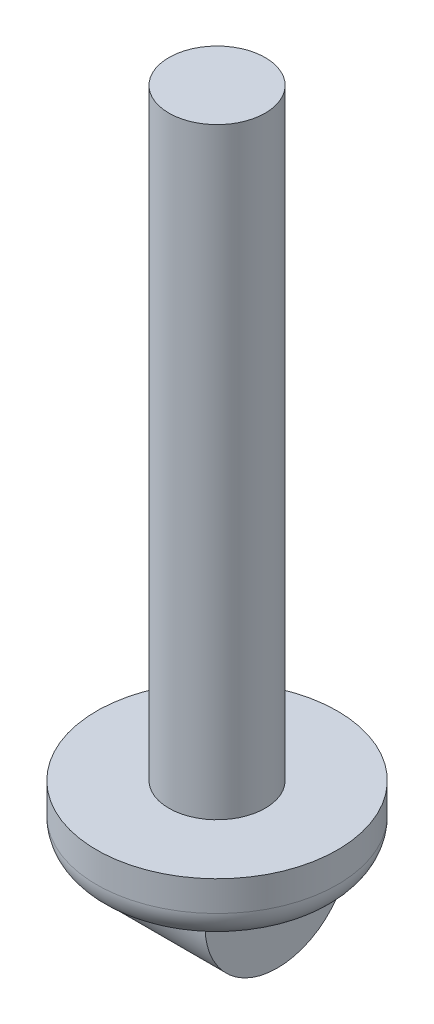
SolidWorks part; units mm, degrees
ref_plane "Front Plane" through (0, 0, 0) normal (0, 0, 1) x (1, 0, 0)
ref_plane "Top Plane" through (0, 0, 0) normal (0, 1, 0) x (1, 0, 0)
ref_plane "Right Plane" through (0, 0, 0) normal (1, 0, 0) x (0, 0, -1)
sketch "Sketch1" plane through (0, 0, 0) normal (0, 1, 0) x (1, 0, 0)
  circle A0 centre (0, 0) radius 4
extrude "Boss-Extrude1" add sketch "Sketch1" along normal blind 50
sketch "Sketch3" plane through (0, 0, 0) normal (0, -1, 0) x (1, 0, 0)
  circle A0 centre (0, 0) radius 10
extrude "Boss-Extrude2" add sketch "Sketch3" along normal blind 5
fillet "Fillet1" radius 2.5 1 edges at (0, -5, -10)
sketch "Sketch4" plane through (0, 0, 0) normal (1, 0, 0) x (0, 0, -1)
  line L0 (-7.5, -5) -> (7.5, -5) construction
  line L1 (-6, -5) -> (6, -5)
  arc A0 (-6, -5) -> (6, -5) centre (0, -5) ccw
  dimension "D1" = 12
extrude "Boss-Extrude3" add sketch "Sketch4" along normal mid plane 10
